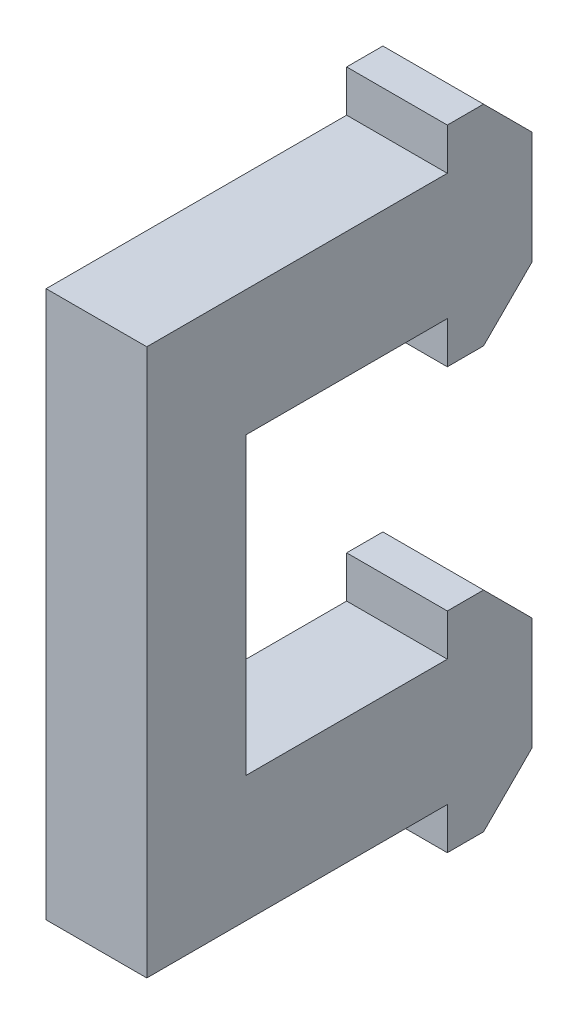
SolidWorks part; units mm, degrees
ref_plane "Front Plane" through (0, 0, 0) normal (0, 0, 1) x (1, 0, 0)
ref_plane "Top Plane" through (0, 0, 0) normal (0, 1, 0) x (1, 0, 0)
ref_plane "Right Plane" through (0, 0, 0) normal (1, 0, 0) x (0, 0, -1)
sketch "Sketch2" plane through (0, 0, 0) normal (1, 0, 0) x (0, 0, -1)
  line L0 (-4.2, 3.125) -> (-14.2, 3.125)
  line L1 (-14.2, 3.125) -> (-14.2, -3.125)
  line L2 (-14.2, -3.125) -> (-4.2, -3.125)
  line L3 (-4.2, 3.125) -> (-4.2, 5.2)
  line L4 (-4.2, 5.2) -> (-2.4, 5.2)
  line L5 (-4.2, -3.125) -> (-4.2, -5.2)
  line L6 (-4.2, -5.2) -> (-2.4, -5.2)
  line L7 (-14.2, 0) -> (0, 0) construction
  line L8 (0, 2.8) -> (0, -2.8)
  line L9 (-2.4, 5.2) -> (0, 2.8)
  line L10 (-2.4, -5.2) -> (0, -2.8)
  point P12 (0, 0)
  dimension "D1" = 6.25
  dimension "D2" = 10.4
  dimension "D3" = 5.2
  dimension "D4" = 1.8
  dimension "D5" = 4.2
  dimension "D6" = 4.2
  dimension "D7" = 5.6
  dimension "D8" = 10
extrude "Boss-Extrude1" add sketch "Sketch2" along normal blind 5
ref_plane "Plane1" through (0, 10.45, 0) normal (0, 1, 0) x (1, 0, 0)
sketch "Sketch3" plane through (0, 0, 0) normal (-1, 0, 0) x (0, 0, 1)
  line L1 (14.2, -3.125) -> (19.1256, -3.125)
  line L2 (14.2, -3.125) -> (14.2, 30.6749)
  line L3 (14.2, 30.6749) -> (19.1256, 30.6749)
  line L4 (19.1256, -3.125) -> (19.1256, 30.6749)
extrude "Boss-Extrude2" add sketch "Sketch3" against normal up to surface (5 mm away) up to face at (5, 0, 5)
mirror "Mirror2" about plane through (0, 10.45, 0) normal (0, 1, 0) of "Boss-Extrude1"
sketch "Sketch4" plane through (0, 0, 0) normal (-1, 0, 0) x (0, 0, 1)
  line L1 (14.2, 24.025) -> (19.1256, 24.025)
  line L2 (14.2, 24.025) -> (14.2, 30.6749)
  line L3 (14.2, 30.6749) -> (19.1256, 30.6749)
  line L4 (19.1256, 24.025) -> (19.1256, 30.6749)
extrude "Cut-Extrude1" cut sketch "Sketch4" against normal through all
equation "\"D3@Sketch2\"=\"D2@Sketch2\"/2"
equation "\"D6@Sketch2\"=\"D5@Sketch2\""
